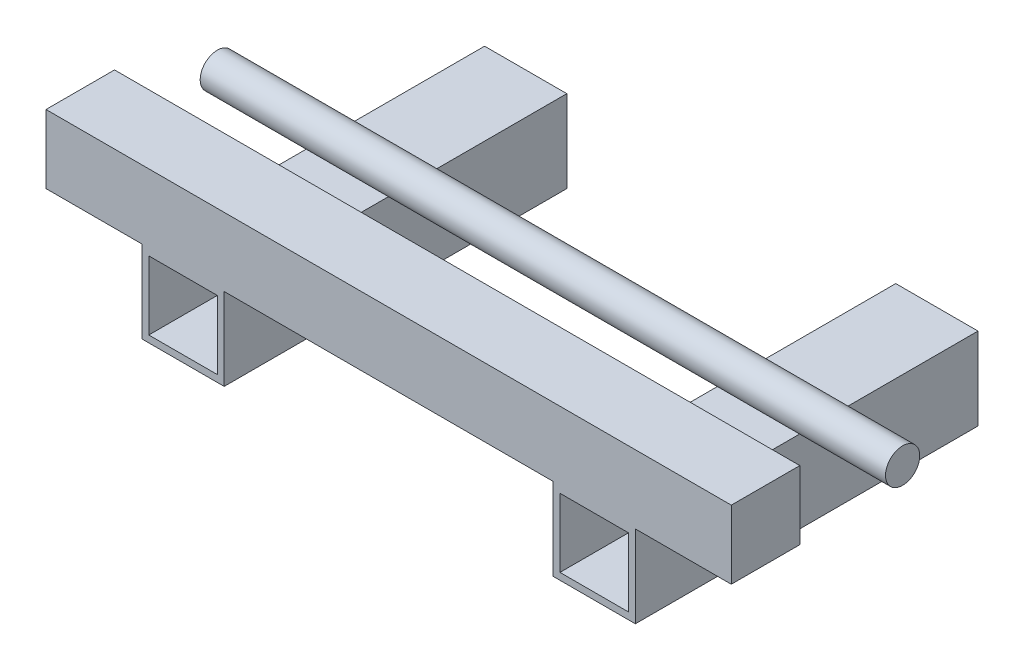
SolidWorks part; units mm, degrees
ref_plane "Front Plane" through (0, 0, 0) normal (0, 0, 1) x (1, 0, 0)
ref_plane "Top Plane" through (0, 0, 0) normal (0, 1, 0) x (1, 0, 0)
ref_plane "Right Plane" through (0, 0, 0) normal (1, 0, 0) x (0, 0, -1)
sketch "Sketch1" plane through (0, 0, 0) normal (0, 0, 1) x (1, 0, 0)
  line L0 (-31.2361, 4.5166) -> (-19.2361, 4.5166)
  line L1 (-30.2361, -6.4834) -> (-20.2361, -6.4834)
  line L2 (-30.2361, -6.4834) -> (-30.2361, 3.5166)
  line L3 (-30.2361, 3.5166) -> (-20.2361, 3.5166)
  line L4 (-20.2361, -6.4834) -> (-20.2361, 3.5166)
  line L5 (29.7639, -6.4834) -> (39.7639, -6.4834)
  line L6 (29.7639, -6.4834) -> (29.7639, 3.5166)
  line L7 (29.7639, 3.5166) -> (39.7639, 3.5166)
  line L8 (39.7639, -6.4834) -> (39.7639, 3.5166)
  line L9 (-19.2361, -7.4834) -> (-19.2361, 4.5166)
  line L10 (-31.2361, -7.4834) -> (-19.2361, -7.4834)
  line L11 (-31.2361, -7.4834) -> (-31.2361, 4.5166)
  line L12 (28.7639, 4.5166) -> (40.7639, 4.5166)
  line L13 (40.7639, -7.4834) -> (40.7639, 4.5166)
  line L14 (28.7639, -7.4834) -> (40.7639, -7.4834)
  line L15 (28.7639, -7.4834) -> (28.7639, 4.5166)
  dimension "D2" = 10
  dimension "D4" = 10
  dimension "D6" = 70
  dimension "D5" = 1
extrude "Boss-Extrude1" add sketch "Sketch1" along normal blind 50
ref_plane "Plane1" through (4.7639, 0, 0) normal (-1, 0, 0) x (0, 0, 1)
sketch "Sketch2" plane through (4.7639, 0, 0) normal (-1, 0, 0) x (0, 0, 1)
  line L0 (50, 4.5166) -> (0, 4.5166) construction
  line L1 (50, 4.5166) -> (50, -7.4834) construction
  line L3 (50, 4.5166) -> (40, 4.5166)
  line L4 (50, 4.5166) -> (50, 14.5166)
  line L5 (50, 14.5166) -> (40, 14.5166)
  line L6 (40, 4.5166) -> (40, 14.5166)
  circle A0 centre (25, 7.0166) radius 2.5
  dimension "D1" = 2.5
  dimension "D2" = 25
  dimension "D3" = 10
  dimension "D4" = 10
extrude "Boss-Extrude2" add sketch "Sketch2" along normal mid plane 100 contours A0 | L6 L5 L4 L3
ref_plane "Plane2" through (0, 0, 25) normal (0, 0, -1) x (-1, 0, 0)
